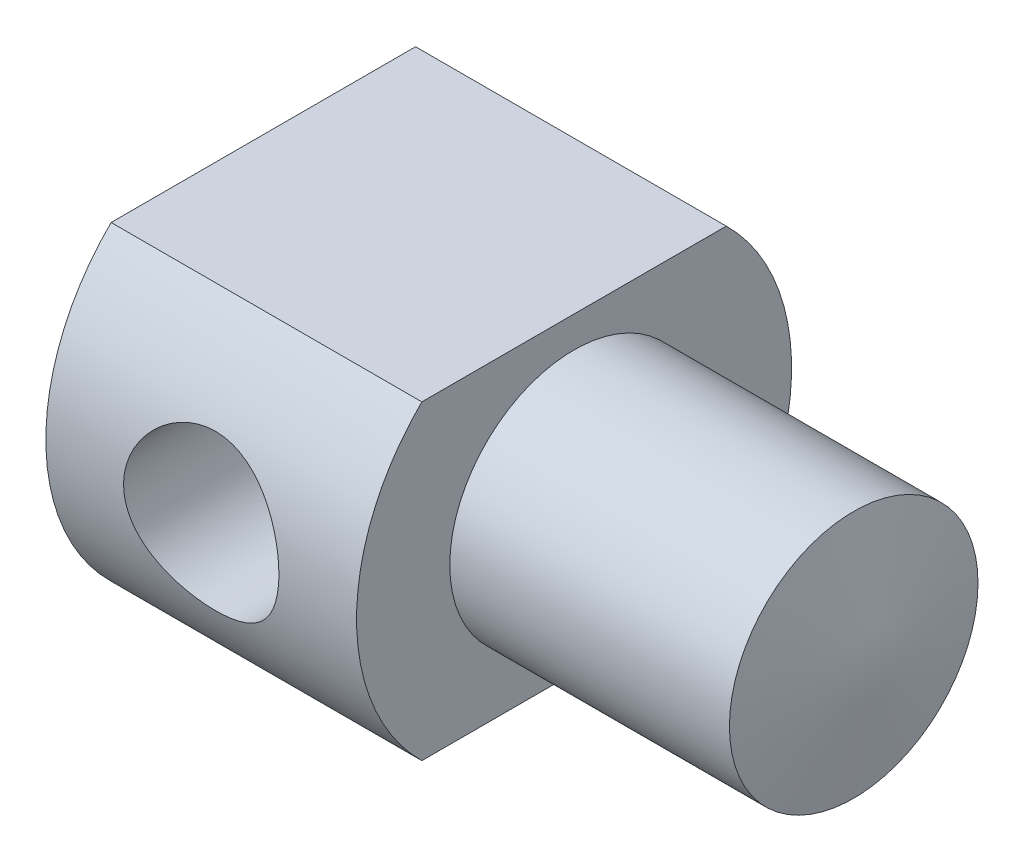
SolidWorks part; units mm, degrees
material "PBT Общее назначение"
ref_plane "Спереди" through (0, 0, 0) normal (0, 0, 1) x (1, 0, 0)
ref_plane "Сверху" through (0, 0, 0) normal (0, 1, 0) x (1, 0, 0)
ref_plane "Справа" through (0, 0, 0) normal (1, 0, 0) x (0, 0, -1)
sketch "Эскиз1" plane through (0, 0, 0) normal (0, 0, 1) x (1, 0, 0)
  line L0 (0, 0) -> (-70.4249, 0) construction
  line L1 (0, 0) -> (-0.7053, 4)
  line L2 (-0.7053, 4) -> (-9.7053, 4)
  line L3 (-9.7053, 4) -> (-9.7053, 7)
  line L4 (-9.7053, 7) -> (-19.7053, 7)
  line L5 (-19.7053, 7) -> (-19.7053, 0)
  line L6 (-19.7053, 0) -> (0, 0)
  dimension "D1" = 80
  dimension "D2" = 4
  dimension "D3" = 9
  dimension "D4" = 7
  dimension "D5" = 10
  dimension "D6" = 19.7053
revolve "Повернуть1" add sketch "Эскиз1" angle 360 about L0
sketch "Эскиз2" plane through (0, 0, 0) normal (0, 0, 1) x (1, 0, 0)
  line L0 (0, 0) -> (-14.7053, 0) construction
  line L1 (-14.7053, 0) -> (-14.7053, 7) construction
  line L2 (-9.7053, 7) -> (-19.7053, 7) construction
  line L3 (-21.8031, -9.0561) -> (-21.8031, -5)
  line L4 (-21.8031, 9.0561) -> (-7.1858, 9.0561)
  line L5 (-21.8031, 9.0561) -> (-21.8031, 5)
  line L6 (-21.8031, 5) -> (-7.1858, 5)
  line L7 (-7.1858, 9.0561) -> (-7.1858, 5)
  line L8 (-21.8031, -5) -> (-7.1858, -5)
  line L9 (-7.1858, -9.0561) -> (-7.1858, -5)
  line L10 (-21.8031, -9.0561) -> (-7.1858, -9.0561)
  circle A0 centre (-14.7053, 0) radius 2.5
  dimension "D1" = 5
  dimension "D2" = 5
extrude "Вырез-Вытянуть1" cut sketch "Эскиз2" against normal mid plane 30
